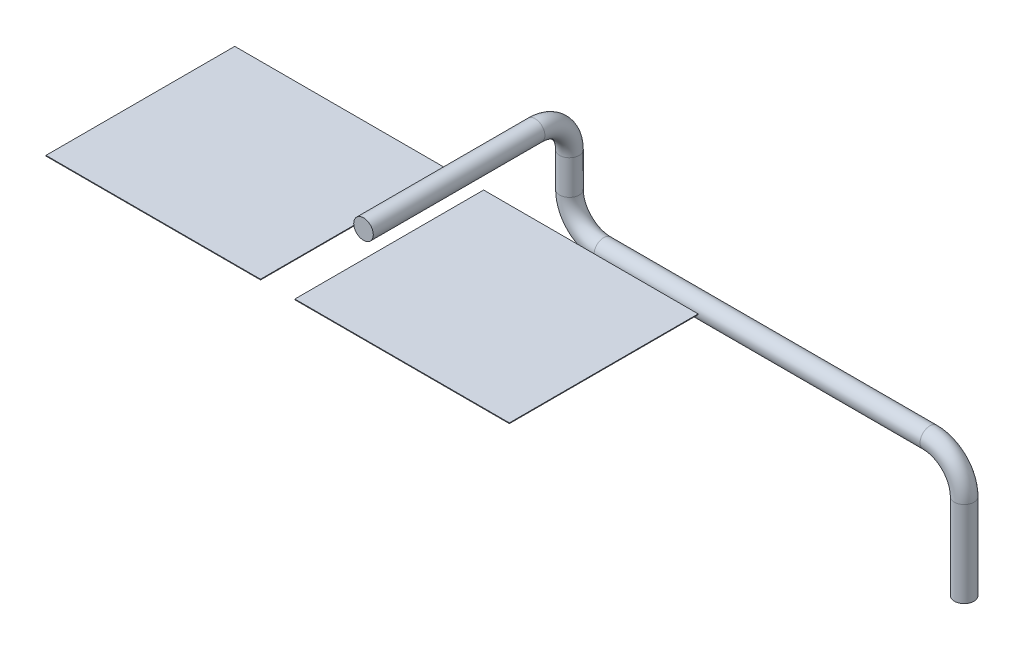
SolidWorks part; units mm, degrees
ref_plane "Спереди" through (0, 0, 0) normal (0, 0, 1) x (1, 0, 0)
ref_plane "Сверху" through (0, 0, 0) normal (0, 1, 0) x (1, 0, 0)
ref_plane "Справа" through (0, 0, 0) normal (1, 0, 0) x (0, 0, -1)
sketch "Эскиз1" plane through (0, 0, 0) normal (0, 1, 0) x (1, 0, 0)
  line L1 (0, 0) -> (12.5, 0)
  line L2 (0, 0) -> (0, 11)
  line L3 (0, 11) -> (12.5, 11)
  line L4 (12.5, 0) -> (12.5, 11)
  line L5 (14.5, 0) -> (27, 0)
  line L6 (14.5, 0) -> (14.5, 11)
  line L7 (14.5, 11) -> (27, 11)
  line L8 (27, 0) -> (27, 11)
  dimension "D1" = 12.5
  dimension "D2" = 11
  dimension "D3" = 2
  dimension "D4" = 12.5
extrude "Бобышка-Вытянуть1" add sketch "Эскиз1" along normal blind 0.04
sketch "Эскиз2" plane through (0, 0, -11) normal (0, 0, -1) x (-1, 0, 0)
  line L0 (-14.5, 0) -> (-12.5, 0) construction
  circle A0 centre (-13.5, 0.57) radius 0.57
  dimension "D1" = 1.14
  dimension "D2" = 0.57
extrude "Бобышка-Вытянуть2" add sketch "Эскиз2" against normal blind 6 separate body
sketch "Эскиз3" plane through (0, 0, -11) normal (0, 0, -1) x (-1, 0, 0)
  circle A0 centre (-13.5, 0.57) radius 0.57 construction
  circle A1 centre (-13.5, 0.57) radius 0.57
extrude "Бобышка-Вытянуть3" add sketch "Эскиз3" along normal blind 2
sketch3d "Трехмерный эскиз2"
  line L0 (13.5, 0.57, -13) -> (13.5, 0.57, -15)
  line L1 (13.5, -1.43, -17) -> (13.5, -3.43, -17)
  line L2 (15.5, -5.43, -17) -> (34.5, -5.43, -17)
  line L3 (36.5, -7.43, -17) -> (36.5, -12.43, -17)
  circle A0 centre (13.5, 0.57, -13) radius 0.57 construction
  circle A1 centre (13.5, 0.57, -13) radius 0.57 construction
  arc A2 (36.5, -7.43, -17) -> (34.5, -5.43, -17) centre (34.5, -7.43, -17) ccw
  arc A3 (15.5, -5.43, -17) -> (13.5, -3.43, -17) centre (15.5, -3.43, -17) ccw
  arc A4 (13.5, -1.43, -17) -> (13.5, 0.57, -15) centre (13.5, -1.43, -15) ccw
  point P2 (13.5, 0.57, -13.57)
  point P4 (13.5, 0.57, -13.57)
  point P11 (36.5, -5.43, -17)
  point P12 (34.5, -7.43, -15)
  point P15 (13.5, -5.43, -17)
  point P16 (15.5, -3.43, -19)
  point P19 (13.5, 0.57, -17)
  point P20 (15.5, -1.43, -15)
  dimension "D5" = 2
  dimension "D1" = 4
  dimension "D2" = 6
  dimension "D3" = 23
  dimension "D4" = 7
sketch "Эскиз5" plane through (0, 0, -13) normal (0, 0, -1) x (-1, 0, 0)
  circle A1 centre (-13.5, 0.57) radius 0.57
  circle A2 centre (-13.5, 0.57) radius 0.57
  dimension "D1" = 0
sweep "По траектории1" add profiles "Эскиз5" path "Трехмерный эскиз2"
